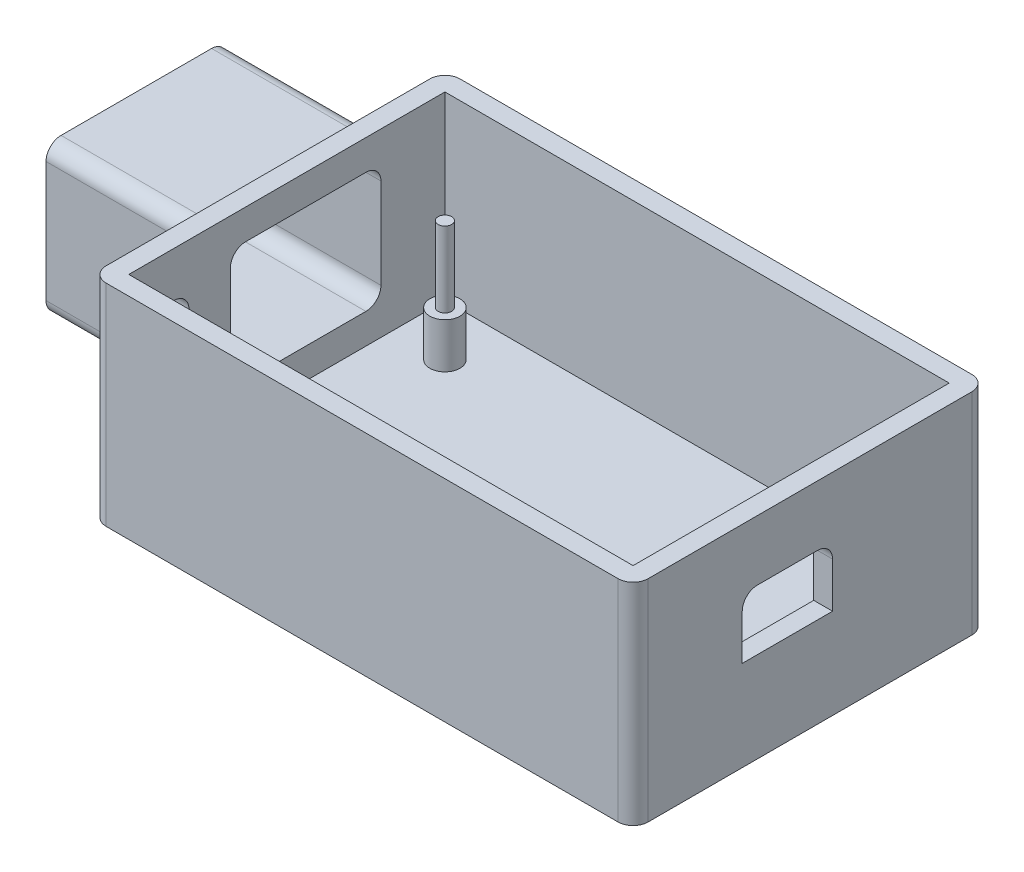
SolidWorks part; units mm, degrees
ref_plane "Front Plane" through (0, 0, 0) normal (0, 0, 1) x (1, 0, 0)
ref_plane "Top Plane" through (0, 0, 0) normal (0, 1, 0) x (1, 0, 0)
ref_plane "Right Plane" through (0, 0, 0) normal (1, 0, 0) x (0, 0, -1)
sketch "Sketch1" plane through (0, 0, 0) normal (0, 1, 0) x (1, 0, 0)
  line L0 (-10.5, -10.5) -> (-10.5, 36.5)
  line L1 (0, 0) -> (51, 0) construction
  line L2 (0, 0) -> (0, 26) construction
  line L3 (0, 26) -> (51, 26) construction
  line L4 (51, 0) -> (51, 26) construction
  line L5 (-10.5, 36.5) -> (61.5, 36.5)
  line L6 (61.5, -10.5) -> (61.5, 36.5)
  line L7 (-10.5, -10.5) -> (61.5, -10.5)
  line L8 (25.5, 36.5) -> (25.5, -10.5) construction
  line L9 (-10.5, 13) -> (61.5, 13) construction
  dimension "D1" = 51
  dimension "D2" = 26
  dimension "D3" = 10.5
extrude "Boss-Extrude1" add sketch "Sketch1" along normal blind 4
sketch "Sketch2" plane through (0, 4, 0) normal (0, 1, 0) x (1, 0, 0)
  line L0 (-3, 13) -> (54, 13) construction
  line L1 (25.5, 29) -> (25.5, -3) construction
  line L8 (-3, 29) -> (-3, -3)
  line L9 (54, 29) -> (-3, 29)
  line L10 (54, -3) -> (54, 29)
  line L11 (-3, -3) -> (54, -3)
  line L12 (-3, 29) -> (-3, -3) construction
  line L13 (54, 29) -> (-3, 29) construction
  line L14 (54, -3) -> (54, 29) construction
  line L15 (-3, -3) -> (54, -3) construction
  circle A4 centre (-1.2, 27.2) radius 0.9
  circle A5 centre (-1.2, -1.2) radius 0.9
  circle A6 centre (52.2, -1.2) radius 0.9
  circle A7 centre (52.2, 27.2) radius 0.9
  dimension "D2" = 1.8
  dimension "D3" = 1.8
  dimension "D4" = 1.8
  dimension "D1" = 7.5
sketch "Sketch3" plane through (0, 4, 0) normal (0, 1, 0) x (1, 0, 0)
  line L0 (61.5, -10.5) -> (61.5, 36.5) construction
  line L1 (-10.5, -10.5) -> (61.5, -10.5) construction
  line L2 (61.5, 36.5) -> (-10.5, 36.5) construction
  line L3 (-10.5, 36.5) -> (-10.5, -10.5) construction
  line L4 (61.5, -10.5) -> (61.5, 36.5)
  line L5 (-10.5, -10.5) -> (61.5, -10.5)
  line L6 (61.5, 36.5) -> (-10.5, 36.5)
  line L7 (-10.5, 36.5) -> (-10.5, -10.5)
  line L8 (59, -8) -> (59, 34)
  line L9 (59, 34) -> (-8, 34)
  line L10 (-8, 34) -> (-8, -8)
  line L11 (-8, -8) -> (59, -8)
  dimension "D1" = 2.5
extrude "Boss-Extrude3" add sketch "Sketch3" along normal blind 24
extrude "Boss-Extrude4" add sketch "Sketch2" along normal blind 16
sketch "Sketch4" plane through (0, 4, 0) normal (0, 1, 0) x (1, 0, 0)
  line L0 (25.5, 34) -> (25.5, -8) construction
  line L1 (59, 34) -> (-8, 34) construction
  line L2 (-8, -8) -> (59, -8) construction
  line L3 (-8, 13) -> (59, 13) construction
  line L4 (-8, 34) -> (-8, -8) construction
  line L5 (59, -8) -> (59, 34) construction
  circle A0 centre (-1.2, 27.2) radius 2
  circle A1 centre (-1.2, -1.2) radius 2
  circle A2 centre (52.2, -1.2) radius 2
  circle A3 centre (52.2, 27.2) radius 2
  dimension "D1" = 4
extrude "Boss-Extrude5" add sketch "Sketch4" along normal blind 6
sketch "Sketch5" plane through (61.5, 0, 0) normal (1, 0, 0) x (0, 0, -1)
  line L1 (-8, 28) -> (-8, 4) construction
  line L7 (4, 20) -> (16, 20)
  line L8 (4, 20) -> (4, 12)
  line L9 (4, 12) -> (16, 12)
  line L10 (16, 20) -> (16, 12)
  line L11 (-8, 4) -> (34, 4) construction
  line L12 (-8, 28) -> (-8, 4) construction
  line L13 (-8, 4) -> (34, 4) construction
  dimension "D1" = 8
  dimension "D2" = 12
  dimension "D3" = 8
  dimension "D4" = 12
extrude "Cut-Extrude1" cut sketch "Sketch5" against normal blind 6
fillet "Fillet2" radius 2 4 edges at (-10.5, 14, 10.5) (-10.5, 14, -36.5) (61.5, 14, -36.5) (61.5, 14, 10.5)
fillet "Fillet3" radius 2 2 edges at (60.25, 20, -4) (60.25, 20, -16)
sketch "Sketch6" plane through (0, 0, 10.5) normal (0, 0, 1) x (1, 0, 0)
  line L0 (-8, 4) -> (59, 4) construction
  line L1 (59, 28) -> (59, 4) construction
  line L2 (-8, 4) -> (59, 4) construction
  line L3 (59, 28) -> (59, 4) construction
  line L5 (28, 24) -> (44, 24)
  line L6 (28, 24) -> (28, 15)
  line L7 (28, 15) -> (44, 15)
  line L8 (44, 24) -> (44, 15)
  dimension "D1" = 16
  dimension "D2" = 9
  dimension "D3" = 15
  dimension "D4" = 11
extrude "Cut-Extrude2" [suppressed] cut sketch "Sketch6" against normal blind 6 contours L7 L8 L5 L6
sketch "Sketch8" [suppressed] plane through (-10.5, 0, 0) normal (-1, 0, 0) x (0, 0, 1)
  line L0 (-34.5, 28) -> (-34.5, 0) construction
  line L1 (-22.5, 20) -> (-10.5, 20)
  line L2 (-22.5, 20) -> (-22.5, 12)
  line L3 (-22.5, 12) -> (-10.5, 12)
  line L4 (-10.5, 20) -> (-10.5, 12)
  line L6 (-34, 4) -> (8, 4) construction
  line L7 (-34, 4) -> (8, 4) construction
  dimension "D1" = 12
  dimension "D2" = 8
  dimension "D3" = 8
  dimension "D4" = 12
sketch "Sketch11" plane through (-10.5, 0, 0) normal (-1, 0, 0) x (0, 0, 1)
  line L0 (-34.5, 28) -> (8.5, 28) construction
  line L1 (-27.5, 26) -> (-3.5, 26)
  line L2 (-27.5, 26) -> (-27.5, 6)
  line L3 (-27.5, 6) -> (-3.5, 6)
  line L4 (-3.5, 26) -> (-3.5, 6)
  line L5 (-34.5, 28) -> (-34.5, 0) construction
  dimension "D1" = 24
  dimension "D2" = 20
  dimension "D3" = 2
  dimension "D4" = 7
extrude "Boss-Extrude7" add sketch "Sketch11" along normal blind 20
sketch "Sketch12" plane through (-8, 0, 0) normal (1, 0, 0) x (0, 0, -1)
  line L0 (27.5, 6) -> (3.5, 6) construction
  line L1 (3.5, 26) -> (27.5, 26) construction
  line L2 (3.5, 6) -> (3.5, 26) construction
  line L3 (27.5, 26) -> (27.5, 6) construction
  line L4 (27.5, 6) -> (3.5, 6) construction
  line L5 (3.5, 26) -> (27.5, 26) construction
  line L6 (3.5, 6) -> (3.5, 26) construction
  line L7 (27.5, 26) -> (27.5, 6) construction
  line L8 (5.5, 8) -> (5.5, 24)
  line L9 (5.5, 24) -> (25.5, 24)
  line L10 (25.5, 24) -> (25.5, 8)
  line L11 (25.5, 8) -> (5.5, 8)
  dimension "D1" = 2
extrude "Cut-Extrude4" cut sketch "Sketch12" against normal blind 20 contours L8 L9 L10 L11
sketch "Sketch13" plane through (-30.5, 0, 0) normal (-1, 0, 0) x (0, 0, 1)
  line L0 (-3.5, 26) -> (-27.5, 26) construction
  line L1 (-23, 20.5) -> (-8, 20.5)
  line L2 (-23, 20.5) -> (-23, 11.5)
  line L3 (-23, 11.5) -> (-8, 11.5)
  line L4 (-8, 20.5) -> (-8, 11.5)
  line L7 (-3.5, 6) -> (-3.5, 26) construction
  dimension "D1" = 15
  dimension "D2" = 9
  dimension "D3" = 5.5
  dimension "D4" = 4.5
extrude "Cut-Extrude5" cut sketch "Sketch13" against normal blind 20
fillet "Fillet4" radius 2 4 edges at (-18, 8, -25.5) (-18, 24, -25.5) (-18, 24, -5.5) (-18, 8, -5.5)
fillet "Fillet5" radius 2 4 edges at (-20.5, 6, -3.5) (-20.5, 26, -3.5) (-20.5, 6, -27.5) (-20.5, 26, -27.5)
sketch "Sketch14" plane through (-10.5, 0, 0) normal (-1, 0, 0) x (0, 0, 1)
  line L0 (-34.5, 0) -> (8.5, 0) construction
  line L1 (0, 22) -> (6, 22)
  line L2 (0, 22) -> (0, 8)
  line L3 (0, 8) -> (6, 8)
  line L4 (6, 22) -> (6, 8)
  dimension "D1" = 6
  dimension "D2" = 14
  dimension "D3" = 8
extrude "Cut-Extrude6" cut sketch "Sketch14" against normal blind 5
fillet "Fillet6" radius 2 4 edges at (-9.25, 22, 6) (-9.25, 22, 0) (-9.25, 8, 6) (-9.25, 8, 0)
